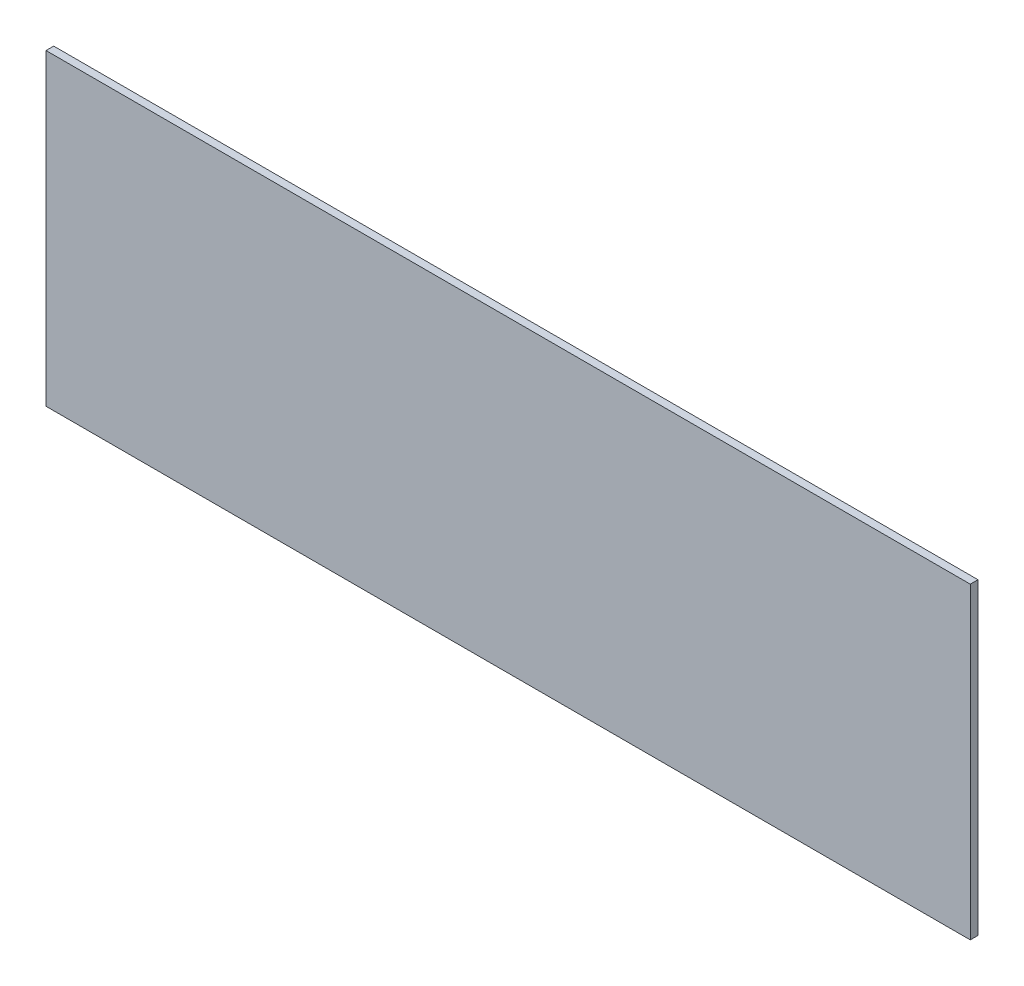
SolidWorks part; units mm, degrees
ref_plane "Front Plane" through (0, 0, 0) normal (0, 0, 1) x (1, 0, 0)
ref_plane "Top Plane" through (0, 0, 0) normal (0, 1, 0) x (1, 0, 0)
ref_plane "Right Plane" through (0, 0, 0) normal (1, 0, 0) x (0, 0, -1)
sketch "Sketch1" plane through (0, 0, 0) normal (0, 0, 1) x (1, 0, 0)
  line L1 (300, 200) -> (-300, 200)
  line L2 (300, 200) -> (300, 0)
  line L3 (300, 0) -> (-300, 0)
  line L4 (-300, 200) -> (-300, 0)
  line L5 (300, 200) -> (-300, 0) construction
  line L6 (300, 0) -> (-300, 200) construction
  point P0 (0, 100)
  dimension "D1" = 600
  dimension "D2" = 200
extrude "Extrude1" add sketch "Sketch1" along normal blind 5
